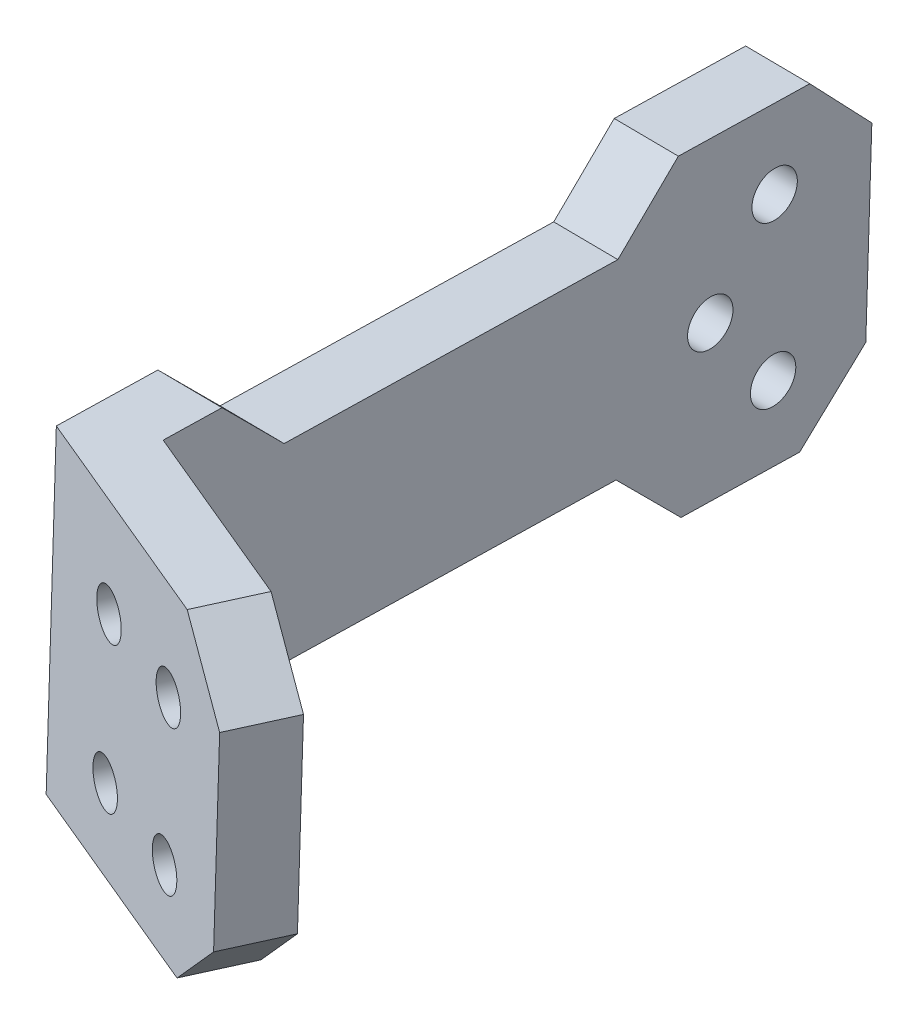
SolidWorks part; units mm, degrees
ref_plane "Front Plane" through (0, 0, 0) normal (0, 0, 1) x (1, 0, 0)
ref_plane "Top Plane" through (0, 0, 0) normal (0, 1, 0) x (1, 0, 0)
ref_plane "Right Plane" through (0, 0, 0) normal (1, 0, 0) x (0, 0, -1)
sketch "Sketch1" plane through (0.6776, 71.7125, -1.6251) normal (0.0094, 0.9997, -0.0227) x (1, -0.0094, 0.0002)
  line L0 (-80.3909, -86.322) -> (-52.3052, -98.0294)
  line L1 (-88.3576, -83.001) -> (-42.7059, -102.0308) construction
  line L2 (-52.3052, -98.0294) -> (-49.862, -92.1682)
  line L3 (-49.862, -92.1682) -> (-74.0409, -82.0893)
  line L4 (-80.3909, -86.322) -> (-80.3909, -11.7008)
  line L5 (-80.3909, -11.7008) -> (-74.0409, -11.7008)
  line L6 (-74.0409, -11.7008) -> (-74.0409, -82.0893)
  dimension "D1" = 6.35
  dimension "D2" = 6.35
extrude "Boss-Extrude1" add sketch "Sketch1" against normal up to surface (31.3937 mm away)
sketch "Sketch2" plane through (-40.1121, 2.559, 96.1984) normal (0.3847, -0.0245, -0.9227) x (-0.923, -0.0102, -0.3846)
  line L4 (-3.6519, 62.3267) -> (75.1536, 63.1332) construction
  line L9 (-3.4804, 48.3793) -> (75.1791, 48.3793) construction
  circle A0 centre (19.1756, 62.5603) radius 2.2479
  circle A1 centre (19.1756, 48.3793) radius 2.2479
  circle A2 centre (30.0985, 62.6721) radius 2.2479
  circle A3 centre (30.0985, 48.3793) radius 2.2479
  dimension "D1" = 4.4958
extrude "Cut-Extrude1" cut sketch "Sketch2" against normal blind 25.4
sketch "Sketch3" plane through (-74.0376, 0.6992, -0.0158) normal (1, -0.0094, 0.0002) x (0.0002, 0, -1)
  circle A2 centre (-19.828, 48.2672) radius 2.2479
  circle A4 centre (-19.828, 64.3087) radius 2.2479
  circle A6 centre (-26.123, 56.3866) radius 2.2479
  dimension "D1" = 4.4958
extrude "Cut-Extrude2" cut sketch "Sketch3" against normal through all
chamfer "Chamfer1" distance 6.35 angle 45 4 edges at (-76.8314, 41.3226, 10.7674) (-76.5348, 72.7068, 10.0562) (-50.7002, 42.9653, 94.1496) (-50.4037, 74.3495, 93.4384)
sketch "Sketch4" plane through (-74.0376, 0.6992, -0.0158) normal (1, -0.0094, 0.0002) x (0.0002, 0, -1)
  line L0 (-74.6192, 73.4434) -> (-68.4134, 67.2376)
  line L1 (-80.4432, 73.5754) -> (-16.4211, 72.1247) construction
  line L2 (-68.4134, 67.2376) -> (-35.367, 66.4888)
  line L3 (-35.367, 66.4888) -> (-29.4362, 72.4196)
  line L4 (-74.6192, 42.0417) -> (-68.4134, 48.2476)
  line L5 (-17.1323, 40.739) -> (-81.1544, 42.1898) construction
  line L6 (-68.4134, 48.2476) -> (-35.367, 47.4987)
  line L7 (-35.367, 47.4987) -> (-28.8734, 41.0051)
  line L8 (-28.8734, 41.0051) -> (-74.6192, 42.0417)
  line L9 (-74.6192, 73.4434) -> (-29.4362, 72.4196)
extrude "Cut-Extrude3" cut sketch "Sketch4" against normal through all
